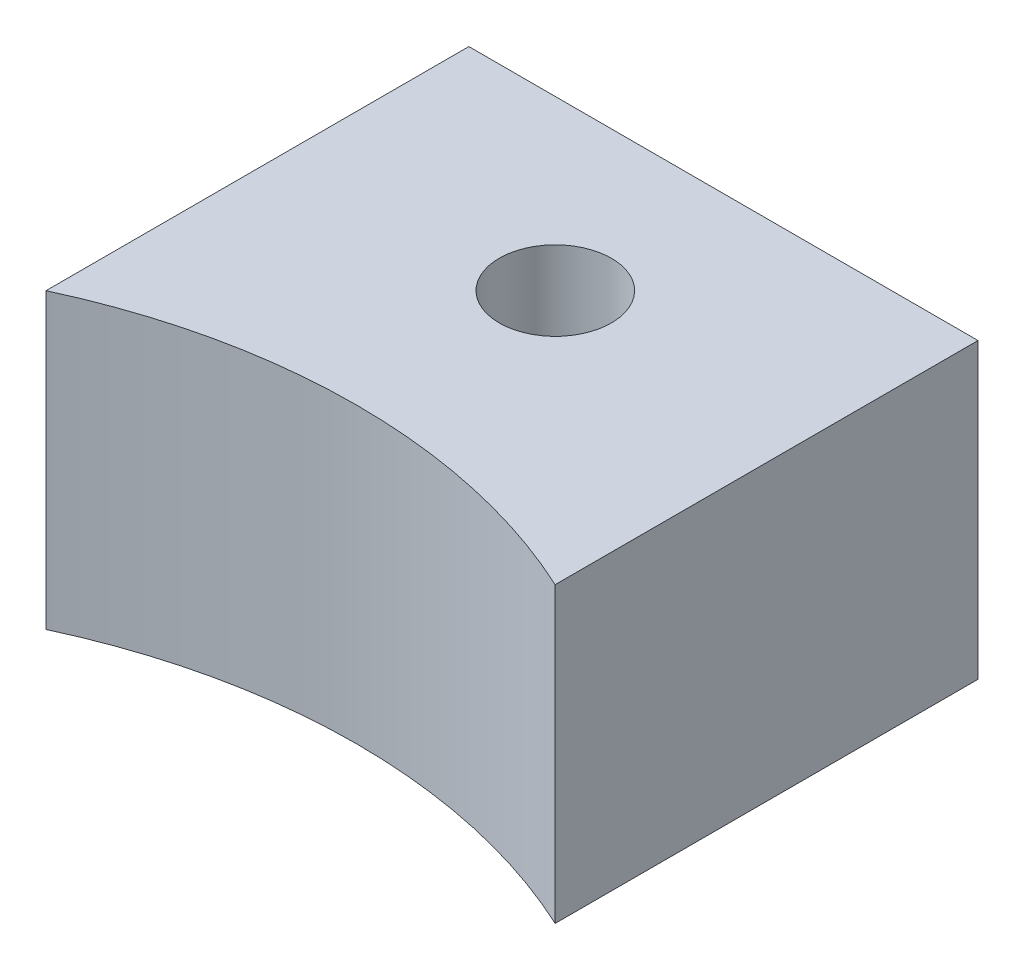
SolidWorks part; units mm, degrees
ref_plane "Plan de face" through (0, 0, 0) normal (0, 0, 1) x (1, 0, 0)
ref_plane "Plan de dessus" through (0, 0, 0) normal (0, 1, 0) x (1, 0, 0)
ref_plane "Plan de droite" through (0, 0, 0) normal (1, 0, 0) x (0, 0, -1)
sketch "Esquisse1" plane through (0, 0, 0) normal (0, 1, 0) x (1, 0, 0)
  line L0 (-14.75, 0) -> (14.75, 0)
  line L1 (14.75, 0) -> (14.75, -24.5)
  line L2 (-14.75, 0) -> (-14.75, -24.5)
  arc A0 (-14.75, -24.5) -> (14.75, -24.5) centre (0, -56.2402) cw
  circle A1 centre (0, -9.7402) radius 3.25
  point P3 (0, 0)
  dimension "D3" = 35
  dimension "D5" = 6.5
  dimension "D1" = 29.5
  dimension "D2" = 24.5
  dimension "D4" = 46.5
extrude "Boss.-Extru.1" add sketch "Esquisse1" along normal blind 17
